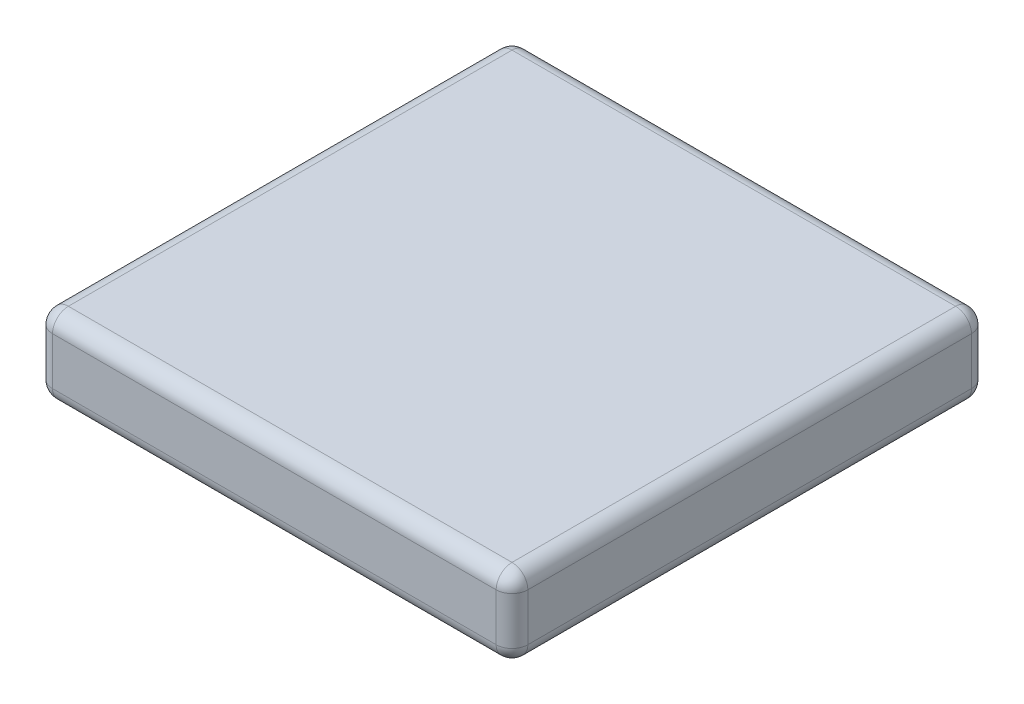
SolidWorks part; units mm, degrees
ref_plane "Front Plane" through (0, 0, 0) normal (0, 0, 1) x (1, 0, 0)
ref_plane "Top Plane" through (0, 0, 0) normal (0, 1, 0) x (1, 0, 0)
ref_plane "Right Plane" through (0, 0, 0) normal (1, 0, 0) x (0, 0, -1)
sketch "Sketch1" plane through (0, 0, 0) normal (0, 1, 0) x (1, 0, 0)
  line L1 (0, 0) -> (30, 0)
  line L2 (0, 0) -> (0, -30)
  line L3 (0, -30) -> (30, -30)
  line L4 (30, 0) -> (30, -30)
  dimension "D1" = 30
  dimension "D2" = 30
extrude "Boss-Extrude1" add sketch "Sketch1" along normal blind 5
fillet "Fillet1" radius 1 12 edges at (0, 2.5, 30) (15, 0, 30) (0, 0, 15) (15, 0, 0) (15, 5, 0) (0, 5, 15) (0, 2.5, 0) (30, 0, 15) (30, 2.5, 30) (30, 5, 15) (15, 5, 30) (30, 2.5, 0)
